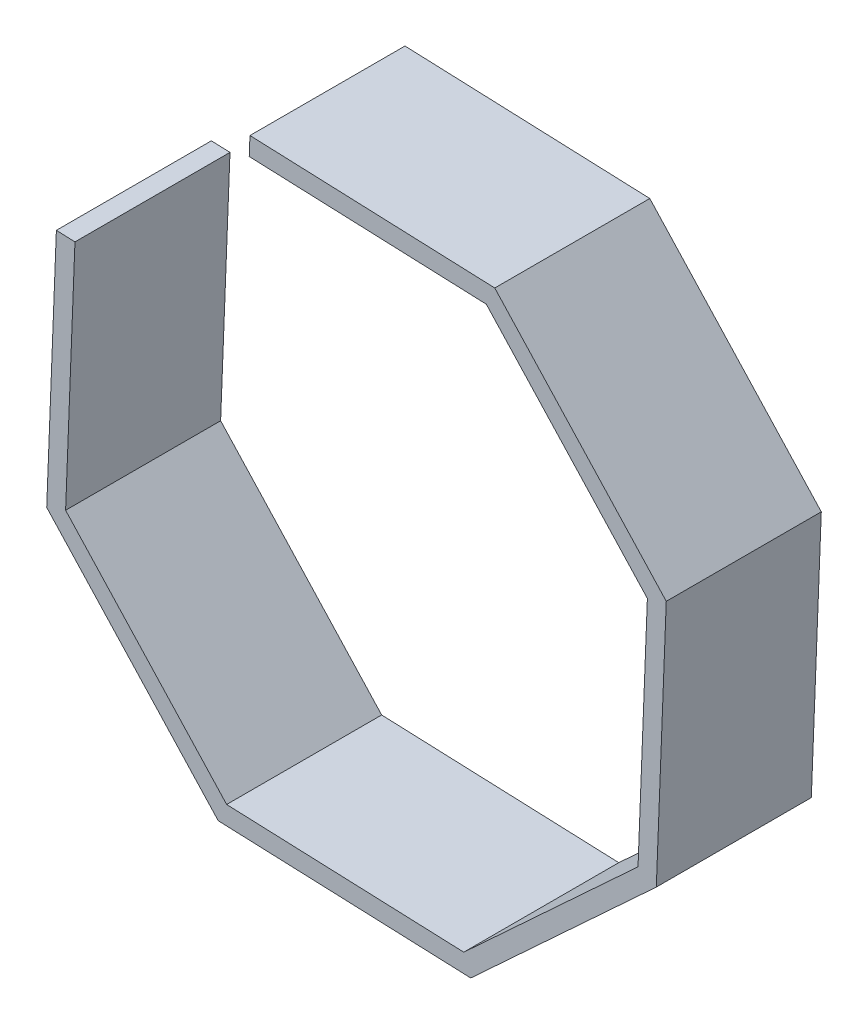
SolidWorks part; units mm, degrees
ref_plane "Front Plane" through (0, 0, 0) normal (0, 0, 1) x (1, 0, 0)
ref_plane "Top Plane" through (0, 0, 0) normal (0, 1, 0) x (1, 0, 0)
ref_plane "Right Plane" through (0, 0, 0) normal (1, 0, 0) x (0, 0, -1)
sketch "Sketch1" plane through (0, 0, 0) normal (0, 0, 1) x (1, 0, 0)
  line L11 (-45.4039, 20.9401) -> (0, 0) construction
  line L12 (20.9401, 45.4039) -> (-17.2985, 46.9123)
  line L14 (-45.4039, 20.9401) -> (-46.9123, -17.2985)
  line L15 (-46.9123, -17.2985) -> (-20.9401, -45.4039)
  line L16 (-20.9401, -45.4039) -> (17.2985, -46.9123)
  line L17 (17.2985, -46.9123) -> (45.4039, -20.9401)
  line L18 (45.4039, -20.9401) -> (46.9123, 17.2985)
  line L19 (46.9123, 17.2985) -> (20.9401, 45.4039)
  line L20 (-17.2985, 46.9123) -> (-45.4039, 20.9401) [skipped]
  line L21 (0, 0) -> (-17.2985, 46.9123) construction
  arc A2 (-45.4039, 20.9401) -> (-17.2985, 46.9123) centre (0, 0) ccw construction
extrude "Extrude-Thin3" add sketch "Sketch1" along normal blind 25 thin
